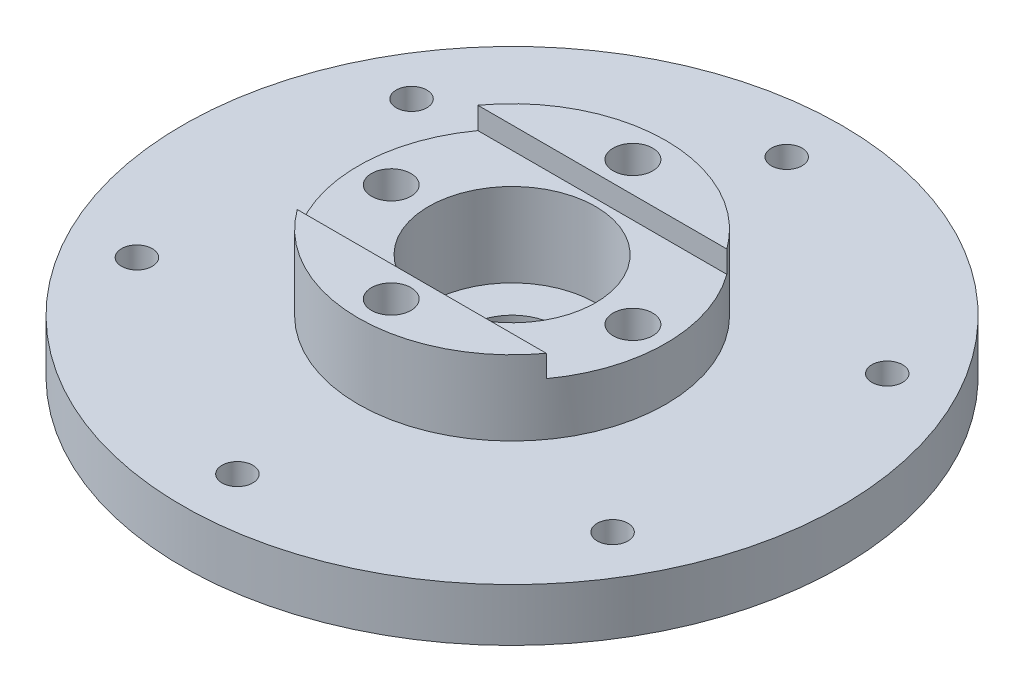
SolidWorks part; units mm, degrees
material "Steel Sectional "
ref_plane "Front Plane" through (0, 0, 0) normal (0, 0, 1) x (1, 0, 0)
ref_plane "Top Plane" through (0, 0, 0) normal (0, 1, 0) x (1, 0, 0)
ref_plane "Right Plane" through (0, 0, 0) normal (1, 0, 0) x (0, 0, -1)
sketch "Sketch1" plane through (0, 0, 0) normal (0, 0, 1) x (1, 0, 0)
  line L0 (0, 0) -> (0, 345.2582) construction
  line L1 (-10, 0) -> (-75, 0)
  line L2 (-75, 0) -> (-75, 12)
  line L3 (-75, 12) -> (-35, 12)
  line L4 (-35, 12) -> (-35, 29)
  line L5 (-35, 29) -> (-19, 29)
  line L6 (-19, 29) -> (-19, 5)
  line L7 (-19, 5) -> (-10, 5)
  line L9 (-10, 5) -> (-10, 0)
  dimension "D1" = 150
  dimension "D2" = 12
  dimension "D3" = 17
  dimension "D4" = 70
  dimension "D5" = 5
  dimension "D6" = 38
  dimension "D7" = 20
revolve "Revolve1" add sketch "Sketch1" angle 360 about L0
sketch "Sketch3" plane through (0, 0, 0) normal (1, 0, 0) x (0, 0, -1)
  line L0 (35, 29) -> (-35, 29) construction
  line L1 (-20.55, 24) -> (20.55, 24)
  line L2 (-20.55, 24) -> (-20.55, 29)
  line L3 (-20.55, 29) -> (20.55, 29)
  line L4 (20.55, 24) -> (20.55, 29)
  line L5 (-20.55, 24) -> (20.55, 29) construction
  line L6 (-20.55, 29) -> (20.55, 24) construction
  point P0 (0, 26.5)
  dimension "D1" = 41.1
  dimension "D2" = 5
extrude "Extrude2" cut sketch "Sketch3" against normal mid plane 120
sketch "Sketch2" plane through (0, 0, 0) normal (0, -1, 0) x (1, 0, 0)
  circle A0 centre (-27.5, 0) radius 4.5
  circle A1 centre (0, -27.5) radius 4.5
  circle A2 centre (0, 27.5) radius 4.5
  circle A3 centre (0, 0) radius 27.5 construction
  circle A4 centre (27.5, 0) radius 4.5
  dimension "D1" = 9
  dimension "D2" = 55
extrude "Extrude1" cut sketch "Sketch2" against normal through all
hole_wizard "M8x1.0 Tapped Hole1" positions "Sketch5" profile "Sketch4" tap size "M8x1.0" standard "Ansi Metric"
sketch "Sketch5" plane through (0, 12, 0) normal (0, 1, 0) x (1, 0, 0)
  circle A0 centre (0, 0) radius 62.5 construction
  point P0 (0, -62.5)
  dimension "D1" = 125
sketch "Sketch4" plane through (0, 12, 62.5) normal (1, 0, 0) x (0, 0, 1)
  line L0 (0, 0) -> (0, 23.103)
  line L1 (0, 23.103) -> (3.5, 21)
  line L2 (3.5, 21) -> (3.5, 0)
  line L5 (3.5, 0) -> (0, 0)
  line L10 (0, 23.103) -> (-3.5, 21) construction
  line L11 (0, -6.35) -> (0, 107.95) construction
  dimension "螺纹孔钻头直径" = 7
  dimension "螺纹孔钻头深度" = 21
  dimension "导头角度" = 118
cosmetic thread "Cosmetic Thread1" parameters "D1"=12, "D2"=8
pattern_circular "CirPattern1" count 6 over 360 about axis through (0, 0, 0) along (0, 1, 0) of "M8x1.0 Tapped Hole1"
